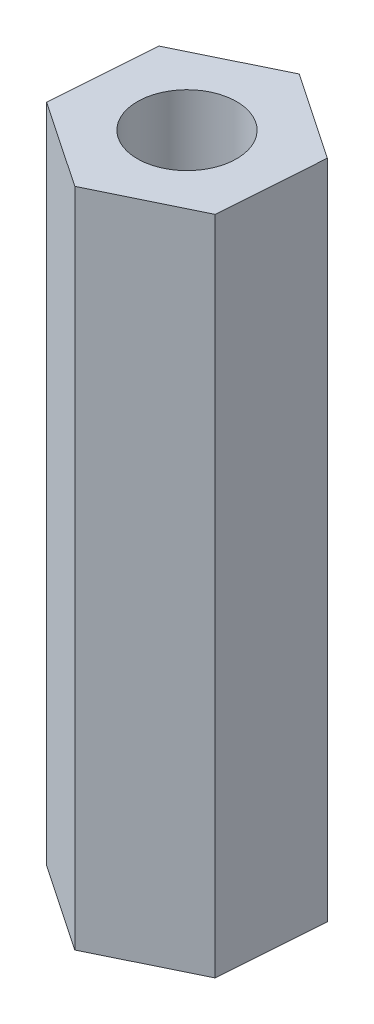
SolidWorks part; units mm, degrees
ref_plane "Front Plane" through (0, 0, 0) normal (0, 0, 1) x (1, 0, 0)
ref_plane "Top Plane" through (0, 0, 0) normal (0, 1, 0) x (1, 0, 0)
ref_plane "Right Plane" through (0, 0, 0) normal (1, 0, 0) x (0, 0, -1)
sketch "Sketch1" plane through (0, 0, 0) normal (0, 1, 0) x (1, 0, 0)
  line L1 (2.6302, -1.7792) -> (2.8559, 1.3882)
  line L2 (2.8559, 1.3882) -> (0.2258, 3.1674)
  line L3 (0.2258, 3.1674) -> (-2.6302, 1.7792)
  line L4 (-2.6302, 1.7792) -> (-2.8559, -1.3882)
  line L5 (-2.8559, -1.3882) -> (-0.2258, -3.1674)
  line L6 (-0.2258, -3.1674) -> (2.6302, -1.7792)
  circle A0 centre (0, 0) radius 2.75 construction
  circle A1 centre (0, 0) radius 1.5
extrude "Boss-Extrude1" add sketch "Sketch1" along normal blind 20
